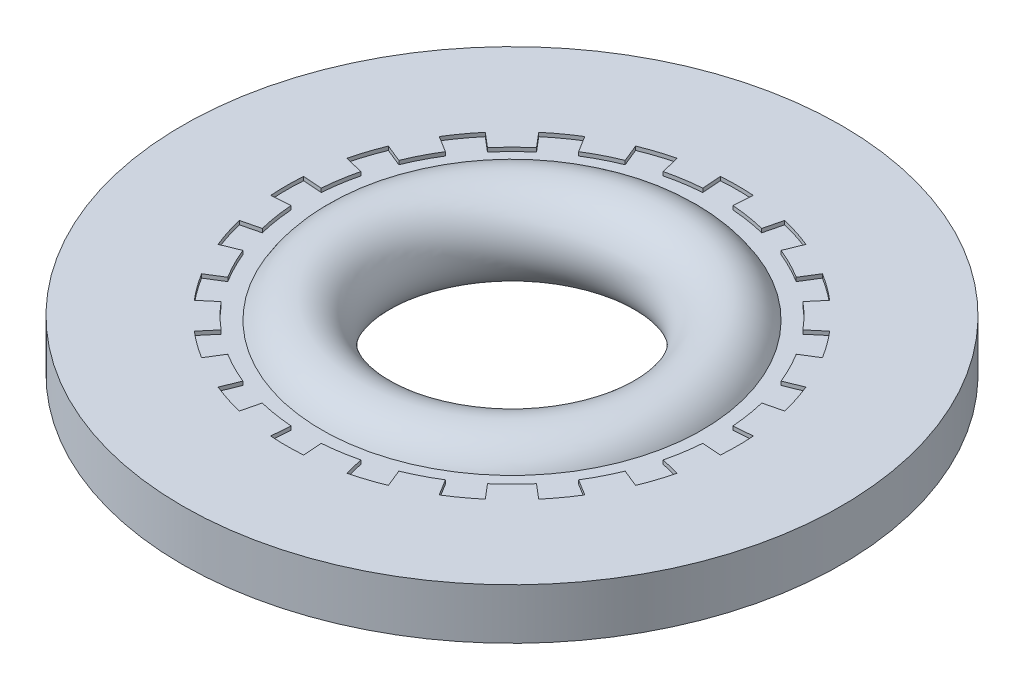
SolidWorks part; units mm, degrees
ref_plane "Front Plane" through (0, 0, 0) normal (0, 0, 1) x (1, 0, 0)
ref_plane "Top Plane" through (0, 0, 0) normal (0, 1, 0) x (1, 0, 0)
ref_plane "Right Plane" through (0, 0, 0) normal (1, 0, 0) x (0, 0, -1)
sketch "Sketch1" plane through (0, 0, 0) normal (0, 0, 1) x (1, 0, 0)
  line L0 (-4.953, 0) -> (4.953, 0) construction
  line L1 (0, 0) -> (0, 0.381) construction
  line L3 (-4.953, 0.381) -> (-2.2987, 0.381)
  line L4 (-4.953, 0.381) -> (-4.953, -0.381)
  line L5 (-4.953, -0.381) -> (-2.2987, -0.381)
  line L6 (-2.2987, 0.381) -> (-2.2987, -0.381)
  circle A0 centre (-2.2987, 0) radius 0.6477
  point P3 (-1.651, 0)
  dimension "D1" = 1.2954
  dimension "D2" = 5.8928
  dimension "ID" = 3.302
  dimension "thickness" = 0.762
  dimension "OD" = 9.906
sketch "Sketch2" plane through (0, 0, 0) normal (0, 0, 1) x (1, 0, 0)
  line L0 (-4.953, 0.381) -> (-4.953, -0.381) construction
  line L2 (-4.953, 0.381) -> (-2.2987, 0.381) construction
  line L3 (-4.953, -0.381) -> (-2.2987, -0.381) construction
  line L4 (-4.953, 0.381) -> (-4.953, -0.381)
  line L5 (-3.1026, 0.381) -> (-3.1026, -0.381)
  line L6 (-4.953, 0.381) -> (-3.1026, 0.381)
  line L7 (-4.953, -0.381) -> (-3.1026, -0.381)
  line L8 (0, 0) -> (0, 0.381) construction
  line L9 (0, 0) -> (0, 0.381) construction
  line L10 (-2.9464, 0.381) -> (-2.9464, -0.381) construction
  circle A0 centre (-2.2987, 0) radius 0.6477 construction
  dimension "D1" = 6.2051
revolve "Revolve1" add sketch "Sketch2" angle 360 about L9
sketch "Sketch3" plane through (0, 0.381, 0) normal (0, 1, 0) x (1, 0, 0)
  line L0 (-0.2268, 3.0943) -> (-0.2476, 3.3793)
  line L1 (0.2268, 3.0943) -> (0.2476, 3.3793)
  circle A0 centre (0, 0) radius 3.3884 construction
  circle A1 centre (0, 0) radius 3.1026 construction
  arc A3 (0.2476, 3.3793) -> (-0.2476, 3.3793) centre (0, 0) ccw
  arc A4 (0.2268, 3.0943) -> (-0.2268, 3.0943) centre (0, 0) ccw
  dimension "D1" = 6.7767
  dimension "D2" = 0.4953
extrude "Cut-Extrude1" cut sketch "Sketch3" against normal through all
pattern_circular "CirPattern1" count 20 over 360 about axis through (0, 0, 0) along (0, 1, 0) of "Cut-Extrude1"
sketch "Sketch4" plane through (0, 0, 0) normal (0, 0, 1) x (1, 0, 0)
  line L3 (-3.3884, -0.3238) -> (-2.8596, -0.3238)
  line L4 (-3.3884, 0.3238) -> (-2.8596, 0.3238)
  line L5 (-3.3884, 0.3238) -> (-3.3884, -0.3238)
  line L6 (0, 0) -> (0, 0.381) construction
  line L7 (0, 0) -> (0, 0.381) construction
  circle A0 centre (-2.2987, 0) radius 0.6477 construction
  arc A1 (-2.8596, -0.3238) -> (-2.8596, 0.3238) centre (-2.2987, 0) ccw
  dimension "D1" = 0.6477
  dimension "D2" = 6.7767
revolve "Revolve2" add sketch "Sketch4" angle 360 about L7
sketch "Sketch5" plane through (0, 0, 0) normal (0, 1, 0) x (1, 0, 0)
  circle A0 centre (0, 0) radius 1.651
  circle A1 centre (0, 0) radius 4.953 construction
  circle A2 centre (0, 0) radius 4.953
equation "\"D1@Sketch1\" = \"thickness@Sketch1\"*1.7"
equation "\"D2@Sketch3\" = \"OD@Sketch1\"/20"
equation "\"D1@Sketch4\" = \"thickness@Sketch1\"*.85"
equation "\"D1@Sketch3\" = \"D2@Sketch1\"*1.15"
equation "\"D1@Sketch2\" = \"D2@Sketch1\"*1.053"
equation "\"D2@Sketch4\" = \"D1@Sketch3\""
